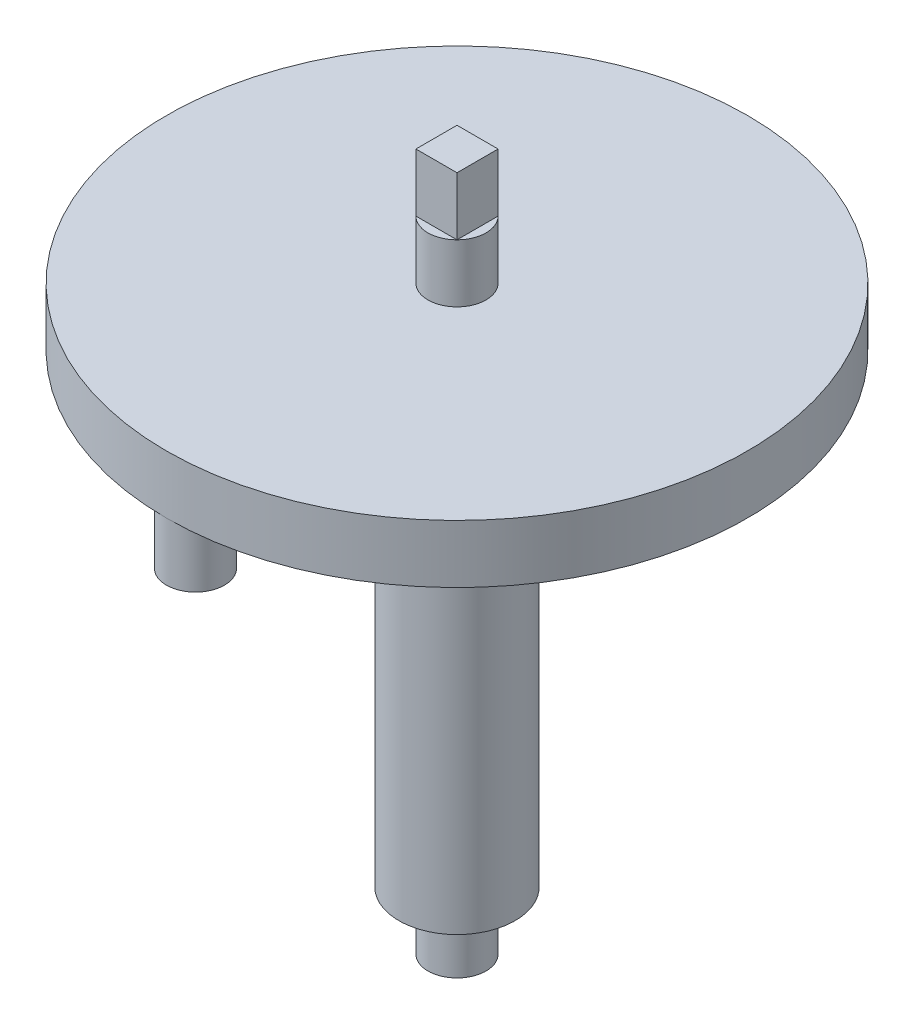
SolidWorks part; units mm, degrees
material "AISI 304"
ref_plane "Front" through (0, 0, 0) normal (0, 0, 1) x (1, 0, 0)
ref_plane "Top" through (0, 0, 0) normal (0, 1, 0) x (1, 0, 0)
ref_plane "Right" through (0, 0, 0) normal (1, 0, 0) x (0, 0, -1)
sketch "Sketch1" plane through (0, 0, 0) normal (0, 1, 0) x (1, 0, 0)
  circle A0 centre (0, 0) radius 25
  circle A1 centre (0, 0) radius 2.5
  dimension "D1" = 50
  dimension "D2" = 5
extrude "Boss-Extrude1" add sketch "Sketch1" along normal blind 5
sketch "Sketch2" plane through (0, 0, 0) normal (0, -1, 0) x (1, 0, 0)
  circle A0 centre (0, 22.5) radius 2.5
  circle A1 centre (0, 0) radius 25 construction
  point P2 (0, 0)
  dimension "D1" = 5
extrude "Boss-Extrude2" add sketch "Sketch2" along normal blind 5
sketch "Sketch3" plane through (0, 0, 0) normal (0, -1, 0) x (1, 0, 0)
  circle A0 centre (0, 0) radius 2.5
  arc A1 (-12.2987, 10.2344) -> (12.2987, 10.2344) centre (0, 0) ccw
  arc A2 (-12.2987, 10.2344) -> (12.2987, 10.2344) centre (0, 32) ccw
  circle A3 centre (0, 0) radius 2.5 construction
  point P8 (0, 0)
  dimension "D1" = 32
  dimension "D3" = 50
  dimension "D2" = 32
extrude "Boss-Extrude3" add sketch "Sketch3" along normal blind 5
sketch "Sketch4" plane through (0, -5, 0) normal (0, -1, 0) x (1, 0, 0)
  circle A0 centre (0, 0) radius 2.5
  circle A1 centre (0, 0) radius 5
  circle A2 centre (0, 0) radius 2.5 construction
  dimension "D1" = 10
extrude "Boss-Extrude4" add sketch "Sketch4" along normal blind 35
sketch "Sketch5" plane through (0, 5, 0) normal (0, 1, 0) x (1, 0, 0)
  circle A0 centre (0, 0) radius 2.5
  circle A1 centre (0, 0) radius 2.5 construction
extrude "Boss-Extrude5" add sketch "Sketch5" against normal offset from surface (55 mm away) 5 from offset 5 up to face at (0, -40, -5) offset beyond the face yes
sketch "Sketch6" plane through (0, 10, 0) normal (0, 1, 0) x (1, 0, 0)
  line L1 (1.7678, 1.7678) -> (-1.7678, 1.7678)
  line L2 (1.7678, 1.7678) -> (1.7678, -1.7678)
  line L3 (1.7678, -1.7678) -> (-1.7678, -1.7678)
  line L4 (-1.7678, 1.7678) -> (-1.7678, -1.7678)
  line L5 (1.7678, 1.7678) -> (-1.7678, -1.7678) construction
  line L6 (1.7678, -1.7678) -> (-1.7678, 1.7678) construction
  circle A0 centre (0, 0) radius 2.5 construction
  point P0 (0, 0)
extrude "Boss-Extrude6" add sketch "Sketch6" along normal blind 5
